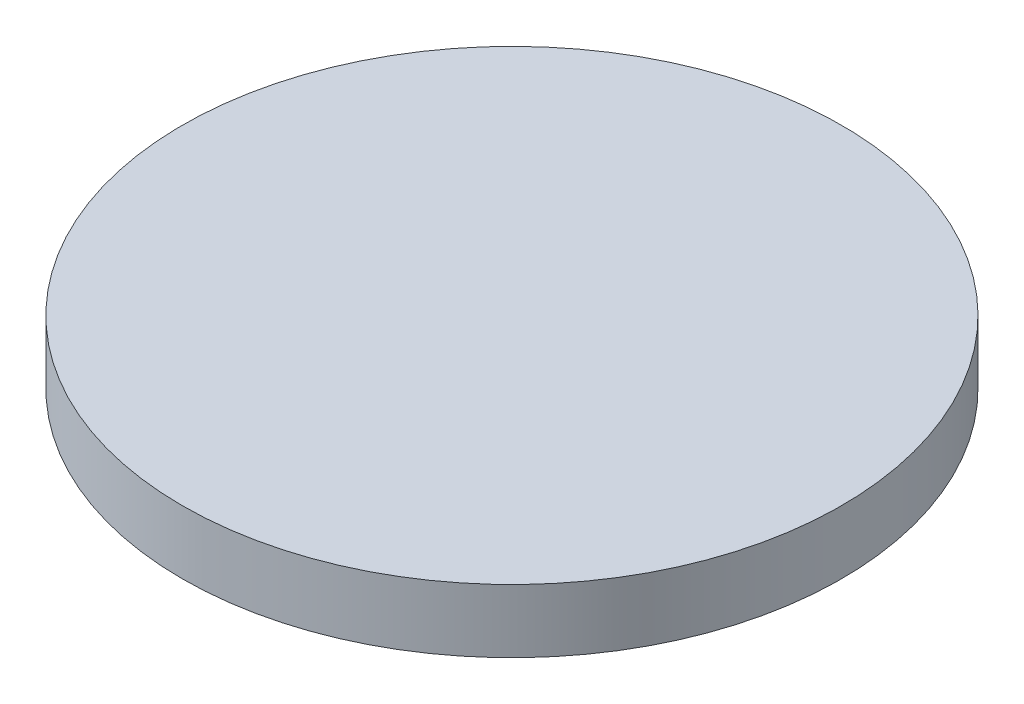
SolidWorks part; units mm, degrees
ref_plane "前视基准面" through (0, 0, 0) normal (0, 0, 1) x (1, 0, 0)
ref_plane "上视基准面" through (0, 0, 0) normal (0, 1, 0) x (1, 0, 0)
ref_plane "右视基准面" through (0, 0, 0) normal (1, 0, 0) x (0, 0, -1)
sketch "草图2" plane through (0, 0, 0) normal (0, 1, 0) x (1, 0, 0)
  line L0 (-6, 0) -> (6, 0) construction
  line L1 (0, 6) -> (0, -6) construction
  circle A0 centre (0, 0) radius 6
  circle A1 centre (0, 4.5) radius 1
  circle A2 centre (-4.5, 0) radius 1
  circle A3 centre (0, -4.5) radius 1
  circle A4 centre (4.5, 0) radius 1
  dimension "D1" = 2
  dimension "D2" = 2
  dimension "D3" = 9
  dimension "D4" = 9
  dimension "D5" = 12
extrude "凸台-拉伸1" add sketch "草图2" along normal blind 2
sketch "草图3" plane through (0, 2, 0) normal (0, 1, 0) x (1, 0, 0)
  circle A0 centre (0, 0) radius 3
  dimension "D1" = 6
extrude "凸台-拉伸2" add sketch "草图3" along normal blind 3
sketch "草图4" plane through (0, 5, 0) normal (0, 1, 0) x (1, 0, 0)
  circle A0 centre (0, 0) radius 8.25
  dimension "D1" = 16.5
extrude "凸台-拉伸3" add sketch "草图4" along normal blind 6.4
fillet "圆角1" radius 3 1 edges at (0, 11.4, 8.25)
fillet "圆角2" radius 0.5 1 edges at (0, 5, 8.25)
sketch "草图5" plane through (0, 11.4, 0) normal (0, 1, 0) x (1, 0, 0)
  line L0 (-13.8049, 0) -> (17.239, 0) construction
  line L1 (0, 13.2763) -> (0, -14.1592) construction
  circle A0 centre (0, 2.5) radius 1
  circle A1 centre (2.5, 0) radius 1
  circle A2 centre (0, -2.5) radius 1
  circle A3 centre (-2.5, 0) radius 1
  dimension "D1" = 2
  dimension "D2" = 2
  dimension "D3" = 5
  dimension "D4" = 5
extrude "切除-拉伸3" cut sketch "草图5" against normal blind 5
sketch "草图7" plane through (0, 11.4, 0) normal (0, 1, 0) x (1, 0, 0)
  circle A0 centre (0, 0) radius 0.8
  dimension "D1" = 1.6
extrude "凸台-拉伸5" add sketch "草图7" along normal blind 4
sketch "草图6" plane through (0, 11.4, 0) normal (0, 1, 0) x (1, 0, 0)
  circle A0 centre (0, 0) radius 26
  dimension "D1" = 52
extrude "凸台-拉伸4" add sketch "草图6" along normal blind 5 separate body
equation "\"m\"= 2"
